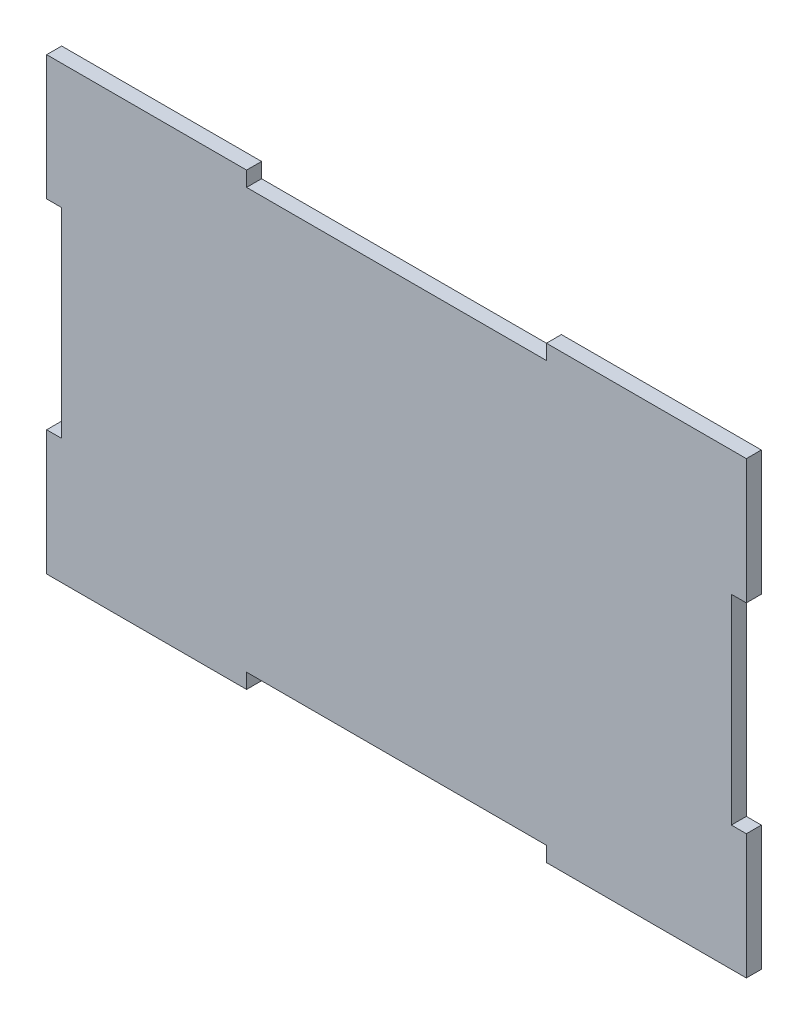
SolidWorks part; units mm, degrees
ref_plane "Спереди" through (0, 0, 0) normal (0, 0, 1) x (1, 0, 0)
ref_plane "Сверху" through (0, 0, 0) normal (0, 1, 0) x (1, 0, 0)
ref_plane "Справа" through (0, 0, 0) normal (1, 0, 0) x (0, 0, -1)
other "Configuration Table"
sketch "Эскиз1" plane through (0, 0, 0) normal (0, 0, 1) x (1, 0, 0)
  line L0 (70, 0) -> (70, 90) construction
  line L1 (0, 0) -> (40, 0)
  line L2 (0, 0) -> (0, 25)
  line L5 (0, 45) -> (140, 45) construction
  line L6 (40, 0) -> (40, 3)
  line L7 (40, 3) -> (100, 3)
  line L8 (137, 25) -> (137, 65)
  line L10 (0, 25) -> (3, 25)
  line L11 (3, 25) -> (3, 65)
  line L12 (140, 25) -> (137, 25)
  line L14 (100, 0) -> (100, 3)
  line L15 (140, 0) -> (140, 25)
  line L16 (140, 0) -> (100, 0)
  line L18 (140, 90) -> (100, 90)
  line L19 (140, 90) -> (140, 65)
  line L20 (100, 90) -> (100, 87)
  line L21 (140, 65) -> (137, 65)
  line L22 (0, 65) -> (3, 65)
  line L23 (40, 87) -> (100, 87)
  line L24 (40, 90) -> (40, 87)
  line L25 (0, 90) -> (0, 65)
  line L26 (0, 90) -> (40, 90)
  point P15 (1.5, 25)
  point P21 (70, 3)
  point P27 (3, 45)
  point P28 (137, 45)
  point P30 (70, 87)
  point P31 (100, 88.5)
  dimension "D1" = 90
  dimension "D2" = 140
  dimension "D3" = 25
  dimension "D4" = 3
  dimension "D5" = 40
  dimension "D6" = 3
  dimension "D7" = 40
  dimension "D8" = 60
extrude "Бобышка-Вытянуть1" add sketch "Эскиз1" along normal blind 3
